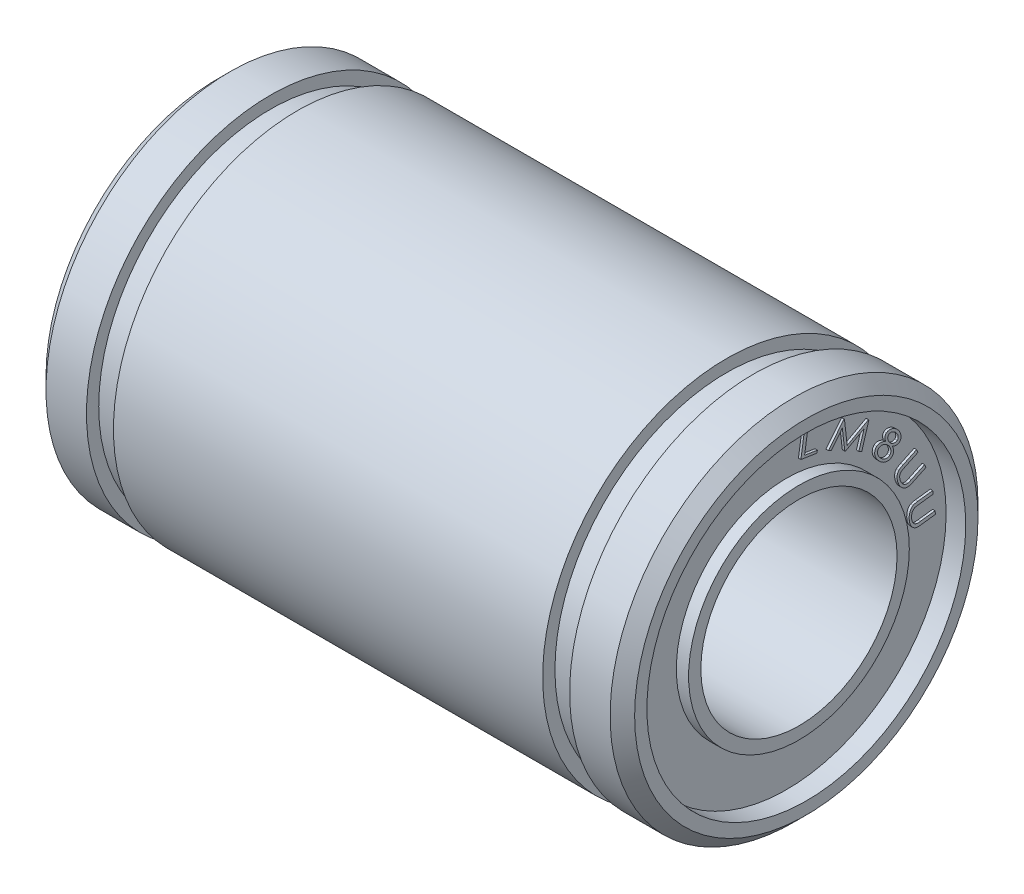
SolidWorks part; units mm, degrees
ref_plane "前基準面" through (0, 0, 0) normal (0, 0, 1) x (1, 0, 0)
ref_plane "上基準面" through (0, 0, 0) normal (0, 1, 0) x (1, 0, 0)
ref_plane "右基準面" through (0, 0, 0) normal (1, 0, 0) x (0, 0, -1)
sketch "Sketch2" plane through (0, 0, 0) normal (1, 0, 0) x (0, 0, -1)
  circle A0 centre (0, 0) radius 7.5
  circle A1 centre (0, 0) radius 6.5
extrude "Boss-Extrude1" add sketch "Sketch2" along normal mid plane 24
sketch "Sketch3" plane through (0, 0, 0) normal (1, 0, 0) x (0, 0, -1)
  circle A0 centre (0, 0) radius 4.5
  circle A1 centre (0, 0) radius 6.5
extrude "Boss-Extrude2" add sketch "Sketch3" along normal offset from surface 0.8 and the other way offset from surface (11.2 mm away) 0.8 up to face at (12, 0, -7.5) other way up to face at (-12, 0, -7.5)
sketch "Sketch4" plane through (0, 0, 0) normal (1, 0, 0) x (0, 0, -1)
  circle A0 centre (0, 0) radius 4.5
  circle A1 centre (0, 0) radius 4
  circle A2 centre (0, 0) radius 4.5 construction
  dimension "D1" = 0.5
extrude "Boss-Extrude3" add sketch "Sketch4" along normal offset from surface 0.5 and the other way offset from surface (11.7 mm away) 0.5 up to face at (11.2, 0, -4.5) offset beyond the face yes other way up to face at (-11.2, 0, -6.5)
chamfer "Chamfer1" distance 0.5 angle 45 2 edges at (-12, 0, -7.5) (12, 0, -7.5)
sketch "Sketch5" plane through (0, 0, 0) normal (0, 0, 1) x (1, 0, 0)
  line L0 (11.5, 7.5) -> (-11.5, 7.5) construction
  line L1 (-9.85, 7.5) -> (-8.75, 7.5)
  line L2 (-9.85, 7.5) -> (-9.85, 7)
  line L3 (-9.85, 7) -> (-8.75, 7)
  line L4 (-8.75, 7.5) -> (-8.75, 7)
  line L5 (0, -8.25) -> (0, 8.25) construction
  line L6 (8.75, 7.5) -> (8.75, 7)
  line L7 (9.85, 7) -> (8.75, 7)
  line L8 (9.85, 7.5) -> (9.85, 7)
  line L9 (9.85, 7.5) -> (8.75, 7.5)
  dimension "D1" = 1.1
  dimension "D2" = 0.5
  dimension "D3" = 8.75
revolve "Cut-Revolve1" cut sketch "Sketch5" angle 360 about axis through (12, 0, 0) along (-1, 0, 0)
sketch "Sketch7" plane through (11.2, 0, 0) normal (1, 0, 0) x (0, 0, -1)
  circle A0 centre (0, 0) radius 5 construction
  text T0 "LM8UU" font "Century Gothic" height 1
sketch "Sketch6" plane through (-11.2, 0, 0) normal (-1, 0, 0) x (0, 0, 1)
  line L0 (0, 4.5) -> (0, 6.5) construction
  circle A0 centre (0, 0) radius 5 construction
  circle A1 centre (0, 0) radius 4.5 construction
  circle A2 centre (0, 0) radius 4.5 construction
  circle A3 centre (0, 0) radius 6.5 construction
  text T0 "LM8UU" font "Century Gothic" height 1
  point P12 (0, 5.5)
  dimension "D1" = 0.5
extrude "Boss-Extrude4" add sketch "Sketch6" along normal blind 0.1
extrude "Boss-Extrude5" add sketch "Sketch7" along normal blind 0.1
